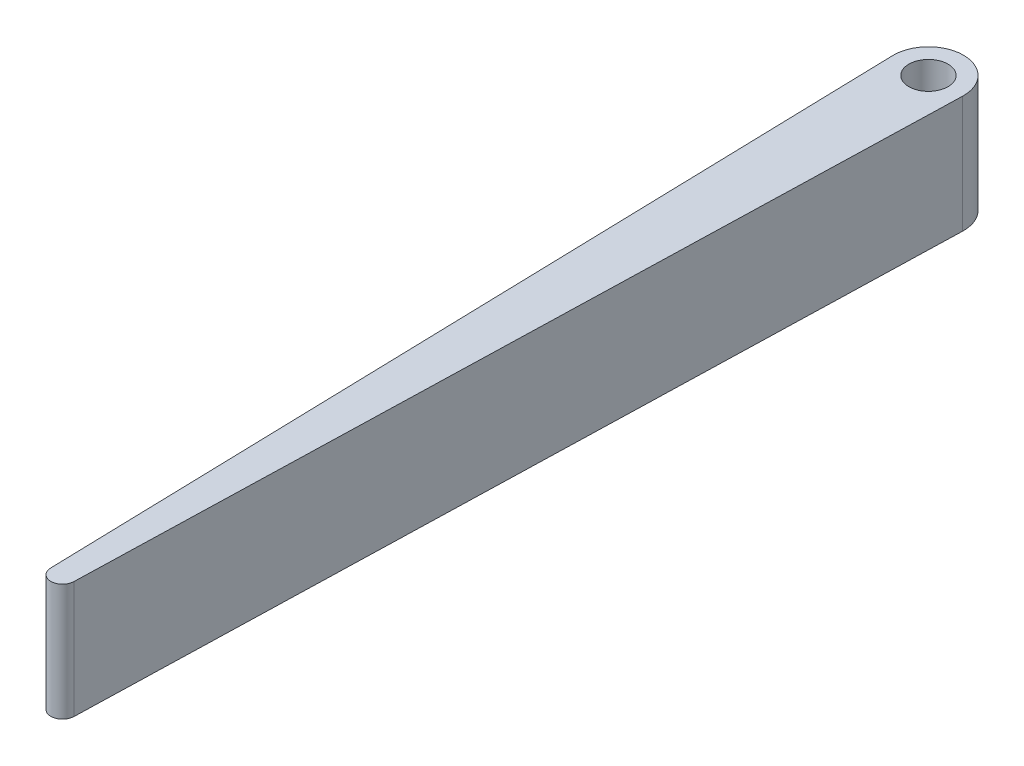
SolidWorks part; units mm, degrees
ref_plane "前视基准面" through (0, 0, 0) normal (0, 0, 1) x (1, 0, 0)
ref_plane "上视基准面" through (0, 0, 0) normal (0, 1, 0) x (1, 0, 0)
ref_plane "右视基准面" through (0, 0, 0) normal (1, 0, 0) x (0, 0, -1)
other "Configuration Table"
sketch "草图1" plane through (0, 0, 0) normal (0, 1, 0) x (1, 0, 0)
  line L0 (-0.0868, -121.9606) -> (-0.1062, -149.2485) construction
  line L1 (-5.9979, -0.1579) -> (-2.1046, -148.0526)
  line L2 (5.9977, -0.1664) -> (1.8939, -148.0555)
  arc A0 (5.9977, -0.1664) -> (-5.9979, -0.1579) centre (0, 0) ccw
  circle A1 centre (0, 0) radius 3.35
  arc A2 (1.8939, -148.0555) -> (-2.1046, -148.0526) centre (-0.1053, -148) cw
  point P12 (-0.1067, -150)
  dimension "D1" = 6.7
  dimension "D2" = 12
  dimension "D3" = 2
  dimension "D4" = 150
extrude "凸台-拉伸1" add sketch "草图1" along normal blind 20
